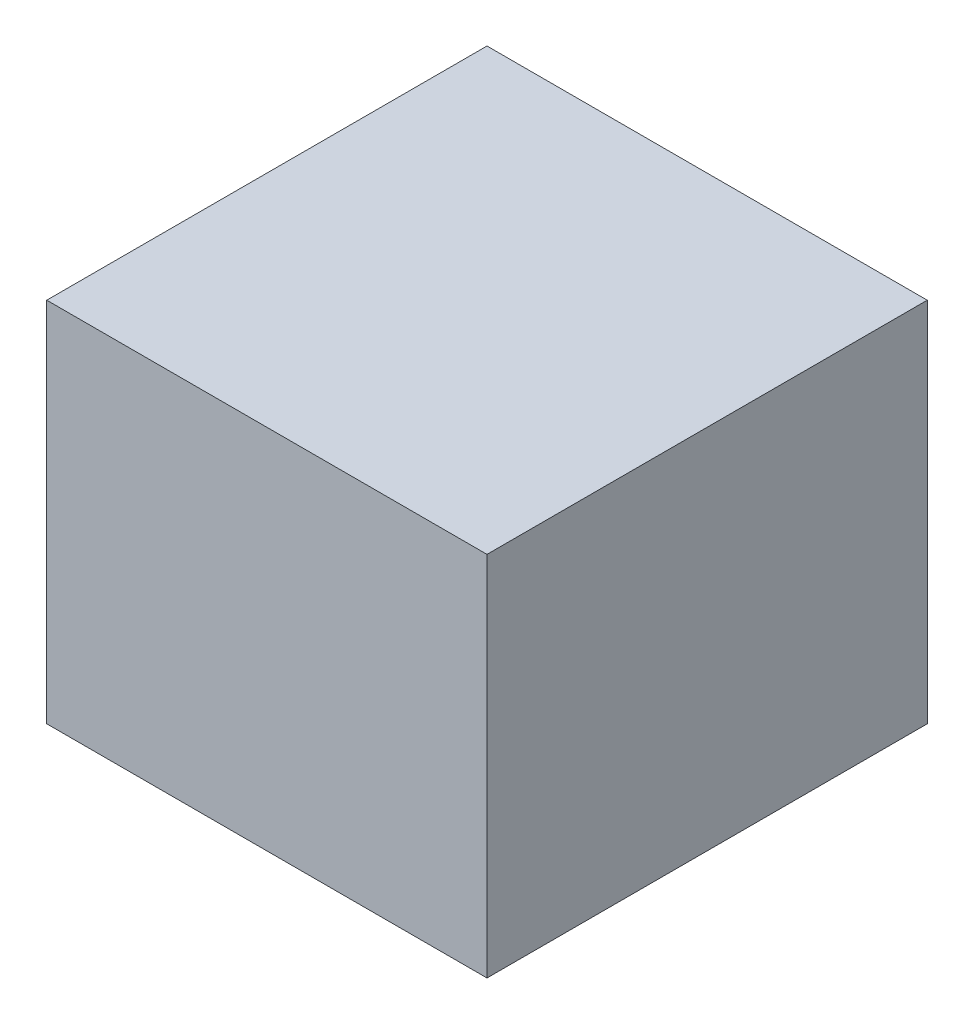
SolidWorks part; units mm, degrees
ref_plane "Спереди" through (0, 0, 0) normal (0, 0, 1) x (1, 0, 0)
ref_plane "Сверху" through (0, 0, 0) normal (0, 1, 0) x (1, 0, 0)
ref_plane "Справа" through (0, 0, 0) normal (1, 0, 0) x (0, 0, -1)
sketch "Эскиз1" plane through (0, 0, 0) normal (0, 1, 0) x (1, 0, 0)
  line L0 (-56.5976, 0) -> (79.1293, 0) construction
  line L1 (-48, 48) -> (48, 48)
  line L2 (-48, 48) -> (-48, -48)
  line L3 (-48, -48) -> (48, -48)
  line L4 (48, 48) -> (48, -48)
  line L5 (0, 44.2588) -> (0, -70.2776) construction
  line L6 (-76.0231, 76.0231) -> (93.1397, -93.1397) construction
  dimension "D1" = 96
sketch "Эскиз3" plane through (0, 0, 0) normal (0, 1, 0) x (1, 0, 0)
  circle A0 centre (0, 0) radius 42.5
  dimension "D1" = 85
extrude "Бобышка-Вытянуть1" add sketch "Эскиз1" against normal blind 80
sketch "Эскиз8" plane through (0, 0, 0) normal (0, 1, 0) x (1, 0, 0)
  circle A0 centre (0, 0) radius 41.25
  dimension "D1" = 82.5
extrude "Вырез-Вытянуть1" [suppressed] cut sketch "Эскиз3" against normal offset from surface (45 mm away) 5
thread "Резьба1" [suppressed] pitch 2 start angle 225, offset 0.5, length 4, pitch 2, diameter 85
ref_plane "Плоскость1" through (30.052, -0.5, 30.052) normal (0.7071, 0, -0.7071) x (0.7071, 0, 0.7071)
sketch "Профиль резьбы1" plane through (30.052, -0.5, 30.052) normal (0.7071, 0, -0.7071) x (0.7071, 0, 0.7071)
  line L0 (0, 0) -> (0, 2) construction
  line L11 (0, 0) -> (0, 1.75)
  line L12 (0, 1.75) -> (-1.0825, 1.125)
  line L13 (-1.0825, 1.125) -> (-1.0825, 0.625)
  line L15 (-1.0825, 0.625) -> (0, 0)
  line L17 (-1.0825, 0.875) -> (0, 0.875) construction
  point P2 (0, 0)
  dimension "Pitch" = 2
  dimension "Profile_Angle" = 60
  dimension "Profile_Land" = 0.5
  dimension "Profile_Height" = 1.0825
sketch "Эскиз6" [suppressed] plane through (0, 0, 0) normal (0, 1, 0) x (1, 0, 0)
  circle A0 centre (0, 0) radius 79.9448
